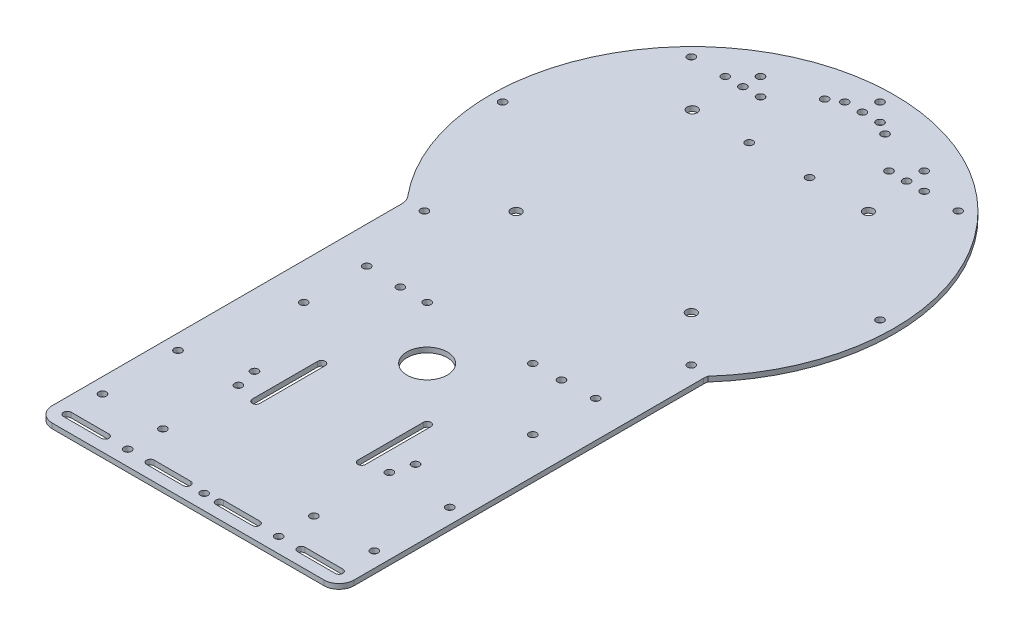
SolidWorks part; units mm, degrees
material "普通碳钢"
ref_plane "前视" through (0, 0, 0) normal (0, 0, 1) x (1, 0, 0)
ref_plane "上视" through (0, 0, 0) normal (0, 1, 0) x (1, 0, 0)
ref_plane "右视" through (0, 0, 0) normal (1, 0, 0) x (0, 0, -1)
sketch "草图1" plane through (0, 0, 0) normal (0, 1, 0) x (1, 0, 0)
  line L0 (394.7344, 186.438) -> (394.7344, 47.5742)
  line L1 (388.7344, 41.5742) -> (280.7344, 41.5742)
  line L2 (274.7344, 47.5742) -> (274.7344, 186.438)
  line L3 (354.2344, 115.5742) -> (354.2344, 89.5742)
  line L4 (357.2344, 89.5742) -> (357.2344, 115.5742)
  line L5 (312.2344, 115.5742) -> (312.2344, 89.5742)
  line L6 (315.2344, 89.5742) -> (315.2344, 115.5742)
  line L7 (373.7344, 46.0742) -> (388.7344, 46.0742)
  line L8 (388.7344, 49.0742) -> (373.7344, 49.0742)
  line L9 (295.7344, 49.0742) -> (280.7344, 49.0742)
  line L10 (280.7344, 46.0742) -> (295.7344, 46.0742)
  line L11 (341.2344, 46.0742) -> (355.7344, 46.0742)
  line L12 (355.7344, 49.0742) -> (341.2344, 49.0742)
  line L13 (328.2344, 49.0742) -> (313.7344, 49.0742)
  line L14 (313.7344, 46.0742) -> (328.2344, 46.0742)
  line L15 (335.1216, 241.5742) -> (335.1216, -105.3995) construction
  arc A0 (394.9445, 188.0119) -> (394.7344, 186.438) centre (400.7344, 186.438) ccw
  arc A1 (388.7344, 41.5742) -> (394.7344, 47.5742) centre (388.7344, 47.5742) ccw
  arc A2 (274.7344, 47.5742) -> (280.7344, 41.5742) centre (280.7344, 47.5742) ccw
  arc A3 (274.7344, 186.438) -> (273.339, 190.2847) centre (268.7344, 186.438) ccw
  arc A4 (394.9445, 188.0119) -> (273.339, 190.2847) centre (335.1216, 241.5742) ccw
  circle A5 centre (370.1216, 276.5742) radius 2
  circle A6 centre (369.7362, 206.5742) radius 2
  circle A7 centre (300.1216, 206.5742) radius 2
  circle A8 centre (313.7344, 157.5742) radius 1.5
  circle A9 centre (355.7344, 157.5742) radius 1.5
  circle A10 centre (380.2344, 133.0742) radius 1.5
  circle A11 centre (380.2344, 158.0742) radius 1.5
  circle A12 centre (364.7344, 61.5742) radius 1.5
  circle A13 centre (388.7344, 61.5742) radius 1.5
  circle A14 centre (364.7344, 91.5742) radius 1.5
  circle A15 centre (388.7344, 91.5742) radius 1.5
  circle A16 centre (304.7344, 61.5742) radius 1.5
  circle A17 centre (280.7344, 61.5742) radius 1.5
  circle A18 centre (304.7344, 91.5742) radius 1.5
  circle A19 centre (280.7344, 91.5742) radius 1.5
  circle A20 centre (334.7344, 316.5742) radius 1.5
  circle A21 centre (281.7014, 294.6072) radius 1.5
  circle A22 centre (259.7344, 241.5742) radius 1.5
  circle A23 centre (281.7014, 188.5412) radius 1.5
  circle A24 centre (387.7674, 188.5412) radius 1.5
  circle A25 centre (409.7344, 241.5742) radius 1.5
  circle A26 centre (387.7674, 294.6072) radius 1.5
  circle A27 centre (322.7344, 306.576) radius 1.5
  circle A28 centre (346.7344, 306.576) radius 1.5
  circle A29 centre (322.7344, 276.576) radius 1.5
  circle A30 centre (346.7344, 276.576) radius 1.5
  circle A31 centre (334.7344, 309.5742) radius 1.5
  circle A32 centre (341.7344, 309.5742) radius 1.5
  circle A33 centre (327.7344, 309.5742) radius 1.5
  circle A34 centre (302.2179, 301.6072) radius 1.5
  circle A35 centre (302.2179, 294.6072) radius 1.5
  circle A36 centre (309.2179, 294.6072) radius 1.5
  circle A37 centre (295.2179, 294.6072) radius 1.5
  circle A38 centre (367.2509, 301.6072) radius 1.5
  circle A39 centre (367.2509, 294.6072) radius 1.5
  circle A40 centre (360.2509, 294.6072) radius 1.5
  circle A41 centre (374.2509, 294.6072) radius 1.5
  circle A42 centre (289.2344, 133.0742) radius 1.5
  circle A43 centre (289.2344, 158.0742) radius 1.5
  circle A44 centre (304.7344, 47.5742) radius 1.5
  circle A45 centre (364.7344, 47.5742) radius 1.5
  circle A46 centre (335.1216, 47.5742) radius 1.5
  circle A47 centre (334.7344, 136.5742) radius 8
  circle A48 centre (300.1216, 276.5742) radius 2
  arc A49 (357.2344, 115.5742) -> (354.2344, 115.5742) centre (355.7344, 115.5742) ccw
  arc A50 (354.2344, 89.5742) -> (357.2344, 89.5742) centre (355.7344, 89.5742) ccw
  arc A51 (312.2344, 89.5742) -> (315.2344, 89.5742) centre (313.7344, 89.5742) ccw
  arc A52 (315.2344, 115.5742) -> (312.2344, 115.5742) centre (313.7344, 115.5742) ccw
  arc A53 (388.7344, 46.0742) -> (388.7344, 49.0742) centre (388.7344, 47.5742) ccw
  arc A54 (373.7344, 49.0742) -> (373.7344, 46.0742) centre (373.7344, 47.5742) ccw
  arc A55 (280.7344, 49.0742) -> (280.7344, 46.0742) centre (280.7344, 47.5742) ccw
  arc A56 (295.7344, 46.0742) -> (295.7344, 49.0742) centre (295.7344, 47.5742) ccw
  arc A57 (355.7344, 46.0742) -> (355.7344, 49.0742) centre (355.7344, 47.5742) ccw
  arc A58 (341.2344, 49.0742) -> (341.2344, 46.0742) centre (341.2344, 47.5742) ccw
  arc A59 (313.7344, 49.0742) -> (313.7344, 46.0742) centre (313.7344, 47.5742) ccw
  arc A60 (328.2344, 46.0742) -> (328.2344, 49.0742) centre (328.2344, 47.5742) ccw
  circle A61 centre (367.1216, 157.5742) radius 1.5
  circle A62 centre (367.1216, 99.5742) radius 1.5
  circle A63 centre (303.1216, 157.5742) radius 1.5
  circle A64 centre (303.1216, 99.5742) radius 1.5
  point P143 (0, 0)
  point P146 (0, 0)
  dimension "D1" = 3
  dimension "D4" = 3
  dimension "D5" = 3
  dimension "D6" = 3
  dimension "D7" = 3
  dimension "D9" = 64
  dimension "D15" = 70
  dimension "D2" = 64
  dimension "D3" = 58
  dimension "D8" = 58
  dimension "D10" = 32
  dimension "D11" = 70
  dimension "D12" = 70
  dimension "D13" = 35
  dimension "D14" = 35
extrude "凸台-拉伸1" add sketch "草图1" along normal blind 2
